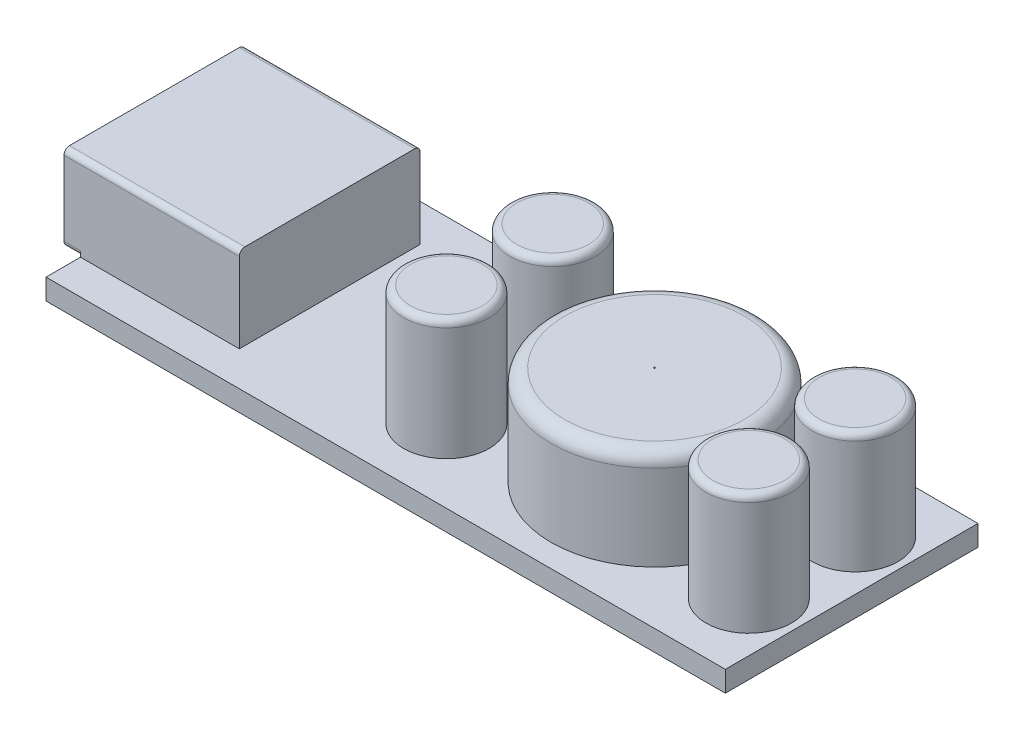
SolidWorks part; units mm, degrees
ref_plane "Спереди XY" through (0, 0, 0) normal (0, 0, 1) x (1, 0, 0)
ref_plane "Сверху XZ" through (0, 0, 0) normal (0, 1, 0) x (1, 0, 0)
ref_plane "Справа ZY" through (0, 0, 0) normal (1, 0, 0) x (0, 0, -1)
sketch "Эскиз1" plane through (0, 0, 0) normal (0, 1, 0) x (1, 0, 0)
  line L1 (-24.6, 9.15) -> (24.6, 9.15)
  line L2 (-24.6, 9.15) -> (-24.6, -9.15)
  line L3 (-24.6, -9.15) -> (24.6, -9.15)
  line L4 (24.6, 9.15) -> (24.6, -9.15)
  line L5 (-24.6, 9.15) -> (24.6, -9.15) construction
  line L6 (-24.6, -9.15) -> (24.6, 9.15) construction
  point P0 (0, 0)
  dimension "D1" = 18.3
  dimension "D2" = 49.2
extrude "Плата модуля быстрой зарядки" add sketch "Эскиз1" along normal blind 1.5
sketch "Эскиз3" plane through (0, 1.5, 0) normal (0, 1, 0) x (1, 0, 0)
  line L1 (-25.8, 6.45) -> (-13.1, 6.45)
  line L2 (-25.8, 6.45) -> (-25.8, -6.65)
  line L3 (-25.8, -6.65) -> (-13.1, -6.65)
  line L4 (-13.1, 6.45) -> (-13.1, -6.65)
  line L5 (-25.8, 6.45) -> (-13.1, -6.65) construction
  line L6 (-25.8, -6.65) -> (-13.1, 6.45) construction
  line L7 (-24.6, 9.15) -> (-24.6, -9.15) construction
  line L8 (24.6, 9.15) -> (-24.6, 9.15) construction
  point P0 (-24.6, 0)
  dimension "D1" = 13.1
  dimension "D2" = 12.7
  dimension "D3" = 1.2
  dimension "D4" = 2.7
extrude "Бобышка-Вытянуть2" add sketch "Эскиз3" along normal blind 6.2
sketch "Эскиз4" plane through (0, 0, 0) normal (0, -1, 0) x (1, 0, 0)
  line L0 (-24.6, -9.15) -> (-24.6, 9.15) construction
  line L1 (-24.6, 4.4) -> (-17.4, 4.4)
  line L2 (-24.6, 4.4) -> (-24.6, -4.4)
  line L3 (-24.6, -4.4) -> (-17.4, -4.4)
  line L4 (-17.4, 4.4) -> (-17.4, -4.4)
  line L5 (-24.6, 4.4) -> (-17.4, -4.4) construction
  line L6 (-24.6, -4.4) -> (-17.4, 4.4) construction
  point P0 (-21, 0)
  point P9 (-24.6, 0)
  point P11 (-24.6, 0)
  dimension "D1" = 7.2
  dimension "D2" = 8.8
extrude "Бобышка-Вытянуть3" add sketch "Эскиз4" along normal blind 3.5
fillet "Скругление2" radius 1 2 edges at (-21, -3.5, 4.4) (-21, -3.5, -4.4)
fillet "Скругление3" radius 0.4 2 edges at (-19.45, 7.7, 6.65) (-19.45, 7.7, -6.45)
sketch "Эскиз5" plane through (0, 1.5, 0) normal (0, 1, 0) x (1, 0, 0)
  line L1 (24.6, 9.15) -> (-24.6, 9.15) construction
  line L2 (-24.6, -9.15) -> (24.6, -9.15) construction
  line L3 (24.6, -9.15) -> (24.6, 9.15) construction
  circle A0 centre (21, 3.85) radius 3.1
  circle A1 centre (21, -3.85) radius 3.1
  circle A2 centre (-0.9, -3.85) radius 3.1
  circle A3 centre (-0.9, 3.85) radius 3.1
  dimension "D1" = 6.2
  dimension "D2" = 5.3
  dimension "D3" = 5.3
  dimension "D4" = 3.6
  dimension "D5" = 25.5
extrude "Бобышка-Вытянуть4" add sketch "Эскиз5" along normal blind 8.7
fillet "Скругление5" radius 0.5 4 edges at (-0.9, 10.2, -0.75) (21, 10.2, -0.75) (21, 10.2, 6.95) (-0.9, 10.2, 6.95)
sketch "Эскиз6" plane through (0, 1.5, 0) normal (0, 1, 0) x (1, 0, 0)
  line L0 (24.6, -9.15) -> (24.6, 9.15) construction
  circle A0 centre (10.3244, 0) radius 0.0536
  circle A1 centre (10.3244, 0) radius 7.5
  point P6 (24.6, 0)
  dimension "D1" = 15
extrude "Бобышка-Вытянуть5" add sketch "Эскиз6" along normal blind 7.2
fillet "Скругление6" radius 1 1 edges at (10.3244, 8.7, 7.5)
sketch "Эскиз7" plane through (-25.8, 0, 0) normal (-1, 0, 0) x (0, 0, 1)
  line L1 (-6.1715, 1.8473) -> (6.3285, 1.8473)
  line L2 (-6.1715, 1.8473) -> (-6.1715, 6.8473)
  line L3 (-6.1715, 6.8473) -> (6.3285, 6.8473)
  line L4 (6.3285, 1.8473) -> (6.3285, 6.8473)
  line L5 (-6.1715, 1.8473) -> (6.3285, 6.8473) construction
  line L6 (-6.1715, 6.8473) -> (6.3285, 1.8473) construction
  point P0 (0, 0)
  dimension "D1" = 5
  dimension "D2" = 12.5
extrude "Вырез-Вытянуть1" cut sketch "Эскиз7" against normal blind 10.2
fillet "Скругление7" radius 0.4 2 edges at (-25.2, 1.5, 6.65) (-25.2, 1.5, -6.45)
